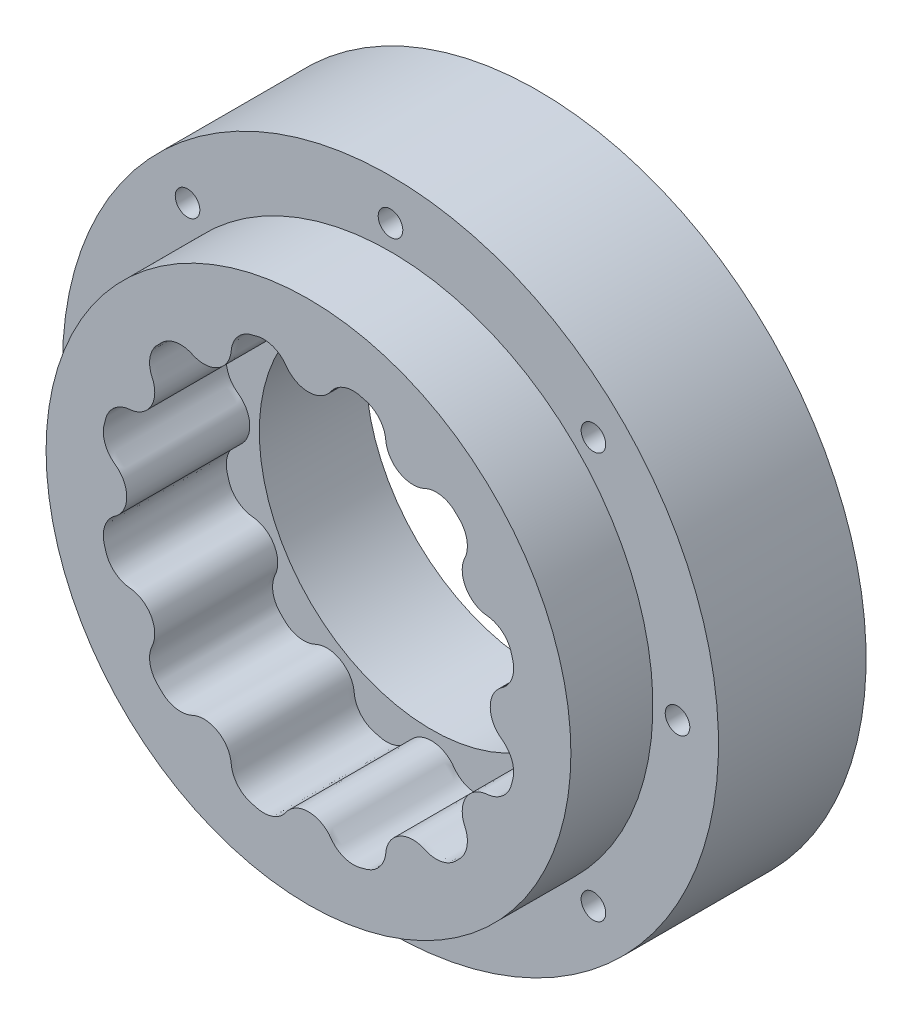
SolidWorks part; units mm, degrees
material "ABS PC"
ref_plane "Front Plane" through (0, 0, 0) normal (0, 0, 1) x (1, 0, 0)
ref_plane "Top Plane" through (0, 0, 0) normal (0, 1, 0) x (1, 0, 0)
ref_plane "Right Plane" through (0, 0, 0) normal (1, 0, 0) x (0, 0, -1)
sketch "Sketch1" plane through (0, 0, 0) normal (0, 0, 1) x (1, 0, 0)
  circle A2 centre (0, 0) radius 32
  spline S1 degree 3 poles (7.0087, -24.7259) (8.3877, -24.335) (9.3004, -23.23) (9.424, -21.8021) (9.424, -21.8014) (9.4241, -21.8) (9.4243, -21.798) (9.4244, -21.7967) (9.4245, -21.796) (9.6443, -19.2549) (11.8531, -17.9797) (14.1636, -19.0598) (14.1643, -19.0601) (14.1655, -19.0607) (14.1673, -19.0616) (14.1686, -19.0621) (14.1692, -19.0624) (15.4522, -19.6623) (16.8504, -19.4359) (17.8785, -18.4617) (17.8853, -18.4553) (17.8988, -18.4425) (17.9188, -18.423) (17.9322, -18.41) (17.9388, -18.4035) (18.0957, -18.2506) (18.2506, -18.0957) (18.4035, -17.9388) (18.41, -17.9322) (18.423, -17.9188) (18.4425, -17.8988) (18.4553, -17.8853) (18.4617, -17.8785) (19.4359, -16.8504) (19.6623, -15.4522) (19.0624, -14.1692) (19.0621, -14.1686) (19.0616, -14.1673) (19.0607, -14.1655) (19.0601, -14.1643) (19.0598, -14.1636) (17.9797, -11.8531) (19.2549, -9.6443) (21.796, -9.4245) (21.7967, -9.4244) (21.798, -9.4243) (21.8, -9.4241) (21.8014, -9.424) (21.8021, -9.424) (23.2132, -9.3019) (24.3108, -8.4068) (24.7141, -7.0491) (24.7168, -7.0401) (24.722, -7.0223) (24.7296, -6.9954) (24.7347, -6.9774) (24.7372, -6.9685) (24.7966, -6.7576) (24.8533, -6.546) (24.9073, -6.3337) (24.9096, -6.3247) (24.9142, -6.3067) (24.921, -6.2796) (24.9254, -6.2615) (24.9276, -6.2524) (25.2571, -4.8749) (24.7541, -3.5509) (23.5931, -2.7397) (23.5926, -2.7393) (23.5915, -2.7385) (23.5898, -2.7373) (23.5887, -2.7365) (23.5881, -2.7362) (21.4974, -1.2753) (21.4974, 1.2753) (23.5881, 2.7362) (23.5887, 2.7365) (23.5898, 2.7373) (23.5915, 2.7385) (23.5926, 2.7393) (23.5931, 2.7397) (24.7541, 3.5509) (25.2571, 4.8749) (24.9276, 6.2524) (24.9254, 6.2615) (24.921, 6.2796) (24.9142, 6.3067) (24.9096, 6.3247) (24.9073, 6.3337) (24.8533, 6.546) (24.7966, 6.7576) (24.7372, 6.9685) (24.7347, 6.9774) (24.7296, 6.9954) (24.722, 7.0223) (24.7168, 7.0401) (24.7141, 7.0491) (24.3108, 8.4068) (23.2132, 9.3019) (21.8021, 9.424) (21.8014, 9.424) (21.8, 9.4241) (21.798, 9.4243) (21.7967, 9.4244) (21.796, 9.4245) (19.2549, 9.6443) (17.9797, 11.8531) (19.0598, 14.1636) (19.0601, 14.1643) (19.0607, 14.1655) (19.0616, 14.1673) (19.0621, 14.1686) (19.0624, 14.1692) (19.6623, 15.4522) (19.4359, 16.8504) (18.4617, 17.8785) (18.4553, 17.8853) (18.4425, 17.8988) (18.423, 17.9188) (18.41, 17.9322) (18.4035, 17.9388) (18.2506, 18.0957) (18.0957, 18.2506) (17.9388, 18.4035) (17.9322, 18.41) (17.9188, 18.423) (17.8988, 18.4425) (17.8853, 18.4553) (17.8785, 18.4617) (16.8504, 19.4359) (15.4522, 19.6623) (14.1692, 19.0624) (14.1686, 19.0621) (14.1673, 19.0616) (14.1655, 19.0607) (14.1643, 19.0601) (14.1636, 19.0598) (11.8531, 17.9797) (9.6443, 19.2549) (9.4245, 21.796) (9.4244, 21.7967) (9.4243, 21.798) (9.4241, 21.8) (9.424, 21.8014) (9.424, 21.8021) (9.3019, 23.2132) (8.4068, 24.3108) (7.0491, 24.7141) (7.0401, 24.7168) (7.0223, 24.722) (6.9954, 24.7296) (6.9774, 24.7347) (6.9685, 24.7372) (6.7576, 24.7966) (6.546, 24.8533) (6.3337, 24.9073) (6.3247, 24.9096) (6.3067, 24.9142) (6.2796, 24.921) (6.2615, 24.9254) (6.2524, 24.9276) (4.8749, 25.2571) (3.5509, 24.7541) (2.7397, 23.5931) (2.7393, 23.5926) (2.7385, 23.5915) (2.7373, 23.5898) (2.7365, 23.5887) (2.7362, 23.5881) (1.2753, 21.4974) (-1.2753, 21.4974) (-2.7362, 23.5881) (-2.7365, 23.5887) (-2.7373, 23.5898) (-2.7385, 23.5915) (-2.7393, 23.5926) (-2.7397, 23.5931) (-3.5509, 24.7541) (-4.8749, 25.2571) (-6.2524, 24.9276) (-6.2615, 24.9254) (-6.2796, 24.921) (-6.3067, 24.9142) (-6.3247, 24.9096) (-6.3337, 24.9073) (-6.546, 24.8533) (-6.7576, 24.7966) (-6.9685, 24.7372) (-6.9774, 24.7347) (-6.9954, 24.7296) (-7.0223, 24.722) (-7.0401, 24.7168) (-7.0491, 24.7141) (-8.4068, 24.3108) (-9.3019, 23.2132) (-9.424, 21.8021) (-9.424, 21.8014) (-9.4241, 21.8) (-9.4243, 21.798) (-9.4244, 21.7967) (-9.4245, 21.796) (-9.6443, 19.2549) (-11.8531, 17.9797) (-14.1636, 19.0598) (-14.1643, 19.0601) (-14.1655, 19.0607) (-14.1673, 19.0616) (-14.1686, 19.0621) (-14.1692, 19.0624) (-15.4522, 19.6623) (-16.8504, 19.4359) (-17.8785, 18.4617) (-17.8853, 18.4553) (-17.8988, 18.4425) (-17.9188, 18.423) (-17.9322, 18.41) (-17.9388, 18.4035) (-18.0957, 18.2506) (-18.2506, 18.0957) (-18.4035, 17.9388) (-18.41, 17.9322) (-18.423, 17.9188) (-18.4425, 17.8988) (-18.4553, 17.8853) (-18.4617, 17.8785) (-19.4359, 16.8504) (-19.6623, 15.4522) (-19.0624, 14.1692) (-19.0621, 14.1686) (-19.0616, 14.1673) (-19.0607, 14.1655) (-19.0601, 14.1643) (-19.0598, 14.1636) (-17.9797, 11.8531) (-19.2549, 9.6443) (-21.796, 9.4245) (-21.7967, 9.4244) (-21.798, 9.4243) (-21.8, 9.4241) (-21.8014, 9.424) (-21.8021, 9.424) (-23.2132, 9.3019) (-24.3108, 8.4068) (-24.7141, 7.0491) (-24.7168, 7.0401) (-24.722, 7.0223) (-24.7296, 6.9954) (-24.7347, 6.9774) (-24.7372, 6.9685) (-24.7966, 6.7576) (-24.8533, 6.546) (-24.9073, 6.3337) (-24.9096, 6.3247) (-24.9142, 6.3067) (-24.921, 6.2796) (-24.9254, 6.2615) (-24.9276, 6.2524) (-25.2571, 4.8749) (-24.7541, 3.5509) (-23.5931, 2.7397) (-23.5926, 2.7393) (-23.5915, 2.7385) (-23.5898, 2.7373) (-23.5887, 2.7365) (-23.5881, 2.7362) (-21.4974, 1.2753) (-21.4974, -1.2753) (-23.5881, -2.7362) (-23.5887, -2.7365) (-23.5898, -2.7373) (-23.5915, -2.7385) (-23.5926, -2.7393) (-23.5931, -2.7397) (-24.7541, -3.5509) (-25.2571, -4.8749) (-24.9276, -6.2524) (-24.9254, -6.2615) (-24.921, -6.2796) (-24.9142, -6.3067) (-24.9096, -6.3247) (-24.9073, -6.3337) (-24.8533, -6.546) (-24.7966, -6.7576) (-24.7372, -6.9685) (-24.7347, -6.9774) (-24.7296, -6.9954) (-24.722, -7.0223) (-24.7168, -7.0401) (-24.7141, -7.0491) (-24.3108, -8.4068) (-23.2132, -9.3019) (-21.8021, -9.424) (-21.8014, -9.424) (-21.8, -9.4241) (-21.798, -9.4243) (-21.7967, -9.4244) (-21.796, -9.4245) (-19.2549, -9.6443) (-17.9797, -11.8531) (-19.0598, -14.1636) (-19.0601, -14.1643) (-19.0607, -14.1655) (-19.0616, -14.1673) (-19.0621, -14.1686) (-19.0624, -14.1692) (-19.6623, -15.4522) (-19.4359, -16.8504) (-18.4617, -17.8785) (-18.4553, -17.8853) (-18.4425, -17.8988) (-18.423, -17.9188) (-18.41, -17.9322) (-18.4035, -17.9388) (-18.2506, -18.0957) (-18.0957, -18.2506) (-17.9388, -18.4035) (-17.9322, -18.41) (-17.9188, -18.423) (-17.8988, -18.4425) (-17.8853, -18.4553) (-17.8785, -18.4617) (-16.8504, -19.4359) (-15.4522, -19.6623) (-14.1692, -19.0624) (-14.1686, -19.0621) (-14.1673, -19.0616) (-14.1655, -19.0607) (-14.1643, -19.0601) (-14.1636, -19.0598) (-11.8531, -17.9797) (-9.6443, -19.2549) (-9.4245, -21.796) (-9.4244, -21.7967) (-9.4243, -21.798) (-9.4241, -21.8) (-9.424, -21.8014) (-9.424, -21.8021) (-9.3019, -23.2132) (-8.4068, -24.3108) (-7.0491, -24.7141) (-7.0401, -24.7168) (-7.0223, -24.722) (-6.9954, -24.7296) (-6.9774, -24.7347) (-6.9685, -24.7372) (-6.7576, -24.7966) (-6.546, -24.8533) (-6.3337, -24.9073) (-6.3247, -24.9096) (-6.3067, -24.9142) (-6.2796, -24.921) (-6.2615, -24.9254) (-6.2524, -24.9276) (-4.8749, -25.2571) (-3.5509, -24.7541) (-2.7397, -23.5931) (-2.7393, -23.5926) (-2.7385, -23.5915) (-2.7373, -23.5898) (-2.7365, -23.5887) (-2.7362, -23.5881) (-1.2753, -21.4974) (1.2753, -21.4974) (2.7362, -23.5881) (2.7365, -23.5887) (2.7373, -23.5898) (2.7385, -23.5915) (2.7393, -23.5926) (2.7397, -23.5931) (3.5606, -24.768) (4.9036, -25.2685) (6.2932, -24.9176) (6.373, -24.8974) (6.5311, -24.8512) (6.7695, -24.7873) (6.9295, -24.7483) (7.0087, -24.7259) (8.3877, -24.335) (9.3004, -23.23) knots -0.001489 0 0 0 0.022862 0.022862 0.022862 0.022874 0.022886 0.022898 0.022898 0.022898 0.055888 0.055888 0.055888 0.0559 0.055912 0.055925 0.055925 0.055925 0.078577 0.078577 0.078577 0.078746 0.078914 0.079083 0.079083 0.079083 0.083044 0.083044 0.083044 0.083213 0.083381 0.08355 0.08355 0.08355 0.106202 0.106202 0.106202 0.106215 0.106227 0.106239 0.106239 0.106239 0.139228 0.139228 0.139228 0.139241 0.139253 0.139265 0.139265 0.139265 0.161918 0.161918 0.161918 0.162087 0.162255 0.162424 0.162424 0.162424 0.166385 0.166385 0.166385 0.166553 0.166722 0.16689 0.16689 0.16689 0.189543 0.189543 0.189543 0.189555 0.189568 0.18958 0.18958 0.18958 0.222569 0.222569 0.222569 0.222581 0.222594 0.222606 0.222606 0.222606 0.245259 0.245259 0.245259 0.245427 0.245596 0.245764 0.245764 0.245764 0.249726 0.249726 0.249726 0.249894 0.250063 0.250231 0.250231 0.250231 0.272884 0.272884 0.272884 0.272896 0.272908 0.272921 0.272921 0.272921 0.30591 0.30591 0.30591 0.305922 0.305935 0.305947 0.305947 0.305947 0.3286 0.3286 0.3286 0.328768 0.328937 0.329105 0.329105 0.329105 0.333066 0.333066 0.333066 0.333235 0.333403 0.333572 0.333572 0.333572 0.356225 0.356225 0.356225 0.356237 0.356249 0.356261 0.356261 0.356261 0.389251 0.389251 0.389251 0.389263 0.389275 0.389288 0.389288 0.389288 0.41194 0.41194 0.41194 0.412109 0.412277 0.412446 0.412446 0.412446 0.416407 0.416407 0.416407 0.416576 0.416744 0.416912 0.416912 0.416912 0.439565 0.439565 0.439565 0.439578 0.43959 0.439602 0.439602 0.439602 0.472591 0.472591 0.472591 0.472604 0.472616 0.472628 0.472628 0.472628 0.495281 0.495281 0.495281 0.49545 0.495618 0.495787 0.495787 0.495787 0.499748 0.499748 0.499748 0.499916 0.500085 0.500253 0.500253 0.500253 0.522906 0.522906 0.522906 0.522918 0.522931 0.522943 0.522943 0.522943 0.555932 0.555932 0.555932 0.555944 0.555957 0.555969 0.555969 0.555969 0.578622 0.578622 0.578622 0.57879 0.578959 0.579127 0.579127 0.579127 0.583089 0.583089 0.583089 0.583257 0.583425 0.583594 0.583594 0.583594 0.606247 0.606247 0.606247 0.606259 0.606271 0.606284 0.606284 0.606284 0.639273 0.639273 0.639273 0.639285 0.639297 0.63931 0.63931 0.63931 0.661963 0.661963 0.661963 0.662131 0.662299 0.662468 0.662468 0.662468 0.666429 0.666429 0.666429 0.666598 0.666766 0.666935 0.666935 0.666935 0.689588 0.689588 0.689588 0.6896 0.689612 0.689624 0.689624 0.689624 0.722614 0.722614 0.722614 0.722626 0.722638 0.72265 0.72265 0.72265 0.745303 0.745303 0.745303 0.745472 0.74564 0.745809 0.745809 0.745809 0.74977 0.74977 0.74977 0.749938 0.750107 0.750275 0.750275 0.750275 0.772928 0.772928 0.772928 0.772941 0.772953 0.772965 0.772965 0.772965 0.805954 0.805954 0.805954 0.805967 0.805979 0.805991 0.805991 0.805991 0.828644 0.828644 0.828644 0.828812 0.828981 0.829149 0.829149 0.829149 0.833111 0.833111 0.833111 0.833279 0.833448 0.833616 0.833616 0.833616 0.856269 0.856269 0.856269 0.856281 0.856294 0.856306 0.856306 0.856306 0.889295 0.889295 0.889295 0.889307 0.88932 0.889332 0.889332 0.889332 0.911985 0.911985 0.911985 0.912153 0.912322 0.91249 0.91249 0.91249 0.916451 0.916451 0.916451 0.91662 0.916788 0.916957 0.916957 0.916957 0.93961 0.93961 0.93961 0.939622 0.939634 0.939647 0.939647 0.939647 0.972636 0.972636 0.972636 0.972648 0.97266 0.972673 0.972673 0.972673 0.995534 0.995534 0.995534 0.997023 0.998511 1 1 1 1.022862 1.022862 1.022862 weights 1 0.881989 0.881989 1 1 1 1 1 1 0.715182 0.715182 1 1 1 1 1 1 0.884361 0.884361 1 1 1 1 1 1 0.999946 0.999946 1 1 1 1 1 1 0.884361 0.884361 1 1 1 1 1 1 0.715182 0.715182 1 1 1 1 1 1 0.884361 0.884361 1 1 1 1 1 1 0.999946 0.999946 1 1 1 1 1 1 0.884361 0.884361 1 1 1 1 1 1 0.715182 0.715182 1 1 1 1 1 1 0.884361 0.884361 1 1 1 1 1 1 0.999946 0.999946 1 1 1 1 1 1 0.884361 0.884361 1 1 1 1 1 1 0.715182 0.715182 1 1 1 1 1 1 0.884361 0.884361 1 1 1 1 1 1 0.999946 0.999946 1 1 1 1 1 1 0.884361 0.884361 1 1 1 1 1 1 0.715182 0.715182 1 1 1 1 1 1 0.884361 0.884361 1 1 1 1 1 1 0.999946 0.999946 1 1 1 1 1 1 0.884361 0.884361 1 1 1 1 1 1 0.715182 0.715182 1 1 1 1 1 1 0.884361 0.884361 1 1 1 1 1 1 0.999946 0.999946 1 1 1 1 1 1 0.884361 0.884361 1 1 1 1 1 1 0.715182 0.715182 1 1 1 1 1 1 0.884361 0.884361 1 1 1 1 1 1 0.999946 0.999946 1 1 1 1 1 1 0.884361 0.884361 1 1 1 1 1 1 0.715182 0.715182 1 1 1 1 1 1 0.884361 0.884361 1 1 1 1 1 1 0.999946 0.999946 1 1 1 1 1 1 0.884361 0.884361 1 1 1 1 1 1 0.715182 0.715182 1 1 1 1 1 1 0.884361 0.884361 1 1 1 1 1 1 0.999946 0.999946 1 1 1 1 1 1 0.884361 0.884361 1 1 1 1 1 1 0.715182 0.715182 1 1 1 1 1 1 0.884361 0.884361 1 1 1 1 1 1 0.999946 0.999946 1 1 1 1 1 1 0.884361 0.884361 1 1 1 1 1 1 0.715182 0.715182 1 1 1 1 1 1 0.884361 0.884361 1 1 1 1 1 1 0.999946 0.999946 1 1 1 1 1 1 0.884361 0.884361 1 1 1 1 1 1 0.715182 0.715182 1 1 1 1 1 1 0.881989 0.881989 1 1 1 1 1 1 0.881989 0.881989 only from (7.0087, -24.7259) to (7.0087, -24.7259)
  dimension "D1" = 64
extrude "Boss-Extrude1" add sketch "Sketch1" along normal blind 15
sketch "Sketch3" plane through (0, 0, 0) normal (0, 0, -1) x (-1, 0, 0)
  circle A0 centre (0, 0) radius 30
  circle A1 centre (0, 0) radius 40
  dimension "D1" = 80
extrude "Boss-Extrude3" add sketch "Sketch3" against normal blind 5
sketch "Sketch4" plane through (0, 0, 0) normal (0, 0, -1) x (-1, 0, 0)
  circle A0 centre (0, 0) radius 40
  circle A1 centre (0, 0) radius 21
  dimension "D1" = 42
extrude "Boss-Extrude4" add sketch "Sketch4" along normal blind 13
sketch "Sketch5" plane through (0, 0, -13) normal (0, 0, -1) x (-1, 0, 0)
  circle A0 centre (0, 35) radius 1.5
  circle A1 centre (24.7487, 24.7487) radius 1.5
  circle A2 centre (35, 0) radius 1.5
  circle A3 centre (24.7487, -24.7487) radius 1.5
  circle A4 centre (0, -35) radius 1.5
  circle A5 centre (-24.7487, -24.7487) radius 1.5
  circle A6 centre (-35, 0) radius 1.5
  circle A7 centre (-24.7487, 24.7487) radius 1.5
  point P19 (0, 0)
  dimension "D2" = 3
  dimension "D1" = 35
  dimension "D3" = 8
extrude "Cut-Extrude1" cut sketch "Sketch5" against normal blind 20
sketch "Sketch6" plane through (0, 0, -13) normal (0, 0, -1) x (-1, 0, 0)
  circle A0 centre (0, 35) radius 2.5
  circle A1 centre (35, 0) radius 2.5
  circle A2 centre (0, -35) radius 2.5
  circle A3 centre (-35, 0) radius 2.5
  point P12 (0, 0)
  dimension "D1" = 5
  dimension "D2" = 4
extrude "Cut-Extrude2" cut sketch "Sketch6" against normal blind 3
